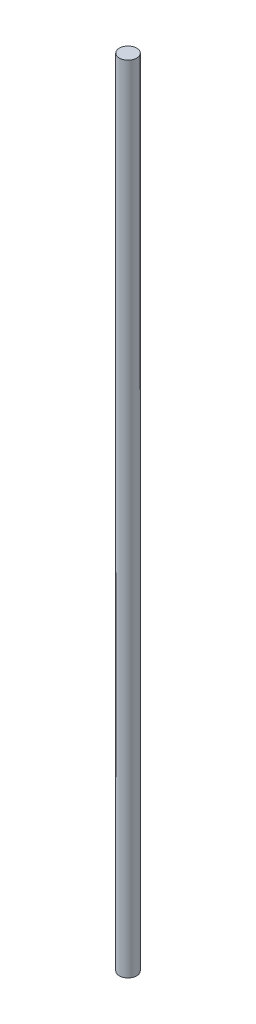
SolidWorks part; units mm, degrees
material "Chrome Stainless Steel"
ref_plane "Front Plane" through (0, 0, 0) normal (0, 0, 1) x (1, 0, 0)
ref_plane "Top Plane" through (0, 0, 0) normal (0, 1, 0) x (1, 0, 0)
ref_plane "Right Plane" through (0, 0, 0) normal (1, 0, 0) x (0, 0, -1)
sketch "Sketch1" plane through (0, 0, 0) normal (0, 1, 0) x (1, 0, 0)
  circle A0 centre (0, 0) radius 5
  dimension "D1" = 10
extrude "Boss-Extrude1" add sketch "Sketch1" along normal blind 458
